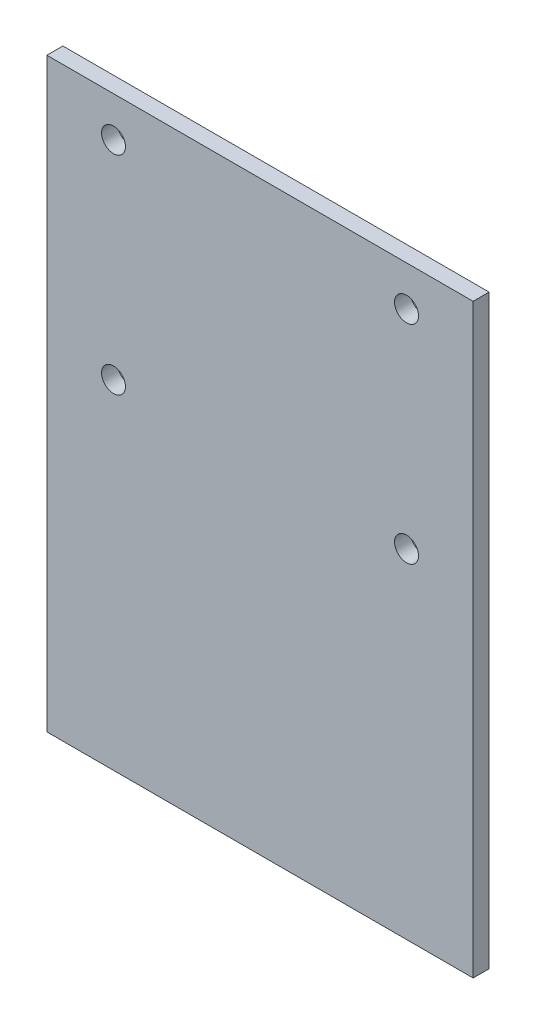
SolidWorks part; units mm, degrees
ref_plane "Plan de face" through (0, 0, 0) normal (0, 0, 1) x (1, 0, 0)
ref_plane "Plan de dessus" through (0, 0, 0) normal (0, 1, 0) x (1, 0, 0)
ref_plane "Plan de droite" through (0, 0, 0) normal (1, 0, 0) x (0, 0, -1)
sketch "Sketch1" plane through (0, 0, 0) normal (0, 0, 1) x (1, 0, 0)
  line L1 (40, -55) -> (-40, -55)
  line L2 (40, -55) -> (40, 55)
  line L3 (40, 55) -> (-40, 55)
  line L4 (-40, -55) -> (-40, 55)
  line L5 (40, -55) -> (-40, 55) construction
  line L6 (40, 55) -> (-40, -55) construction
  point P0 (0, 0)
  dimension "D1" = 80
  dimension "D2" = 110
extrude "Boss-Extrude1" add sketch "Sketch1" along normal blind 3
hole_wizard "Dégagement M41" positions "Sketch2" profile "Sketch3" hole size "M4" standard "ISO" end condition through all
sketch "Sketch2" plane through (0, 0, 3) normal (0, 0, 1) x (1, 0, 0)
  point P0 (27.5, 47.5)
  point P3 (27.5, 8.5)
  point P6 (-27.5, 8.5)
  point P9 (-27.5, 47.5)
sketch "Sketch3" plane through (27.5, 47.5, 3) normal (1, 0, 0) x (0, -1, 0)
  line L0 (0, 0) -> (0, 3)
  line L1 (0, 3) -> (2.25, 3)
  line L2 (2.25, 3) -> (2.25, 0)
  line L5 (2.25, 0) -> (0, 0)
  line L11 (0, -6.35) -> (0, 107.95) construction
  dimension "Diamètre du perçage jusqu'au prochain" = 4.5
  dimension "Profondeur du perçage jusqu'au prochain" = 3
